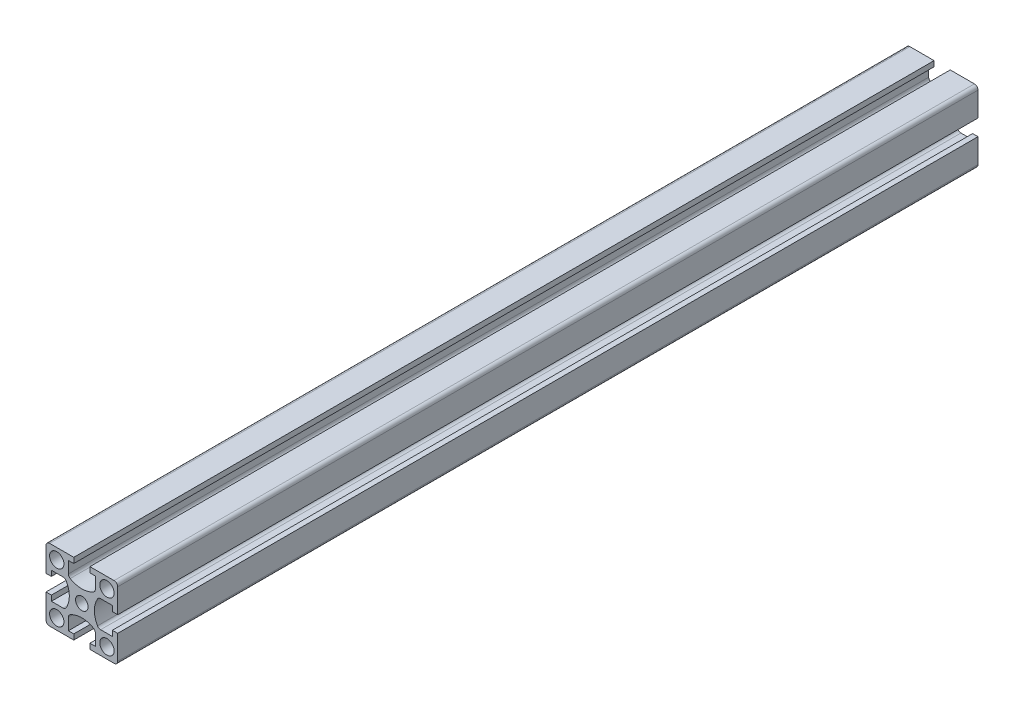
SolidWorks part; units mm, degrees
ref_plane "Front Plane" through (0, 0, 0) normal (0, 0, 1) x (1, 0, 0)
ref_plane "Top Plane" through (0, 0, 0) normal (0, 1, 0) x (1, 0, 0)
ref_plane "Right Plane" through (0, 0, 0) normal (1, 0, 0) x (0, 0, -1)
sketch "Sketch1" plane through (0, 0, 0) normal (0, 0, 1) x (1, 0, 0)
  line L64 (-12.5, 11.25) -> (-12.5, 2.8125)
  line L65 (-12.5, 2.8125) -> (-10.625, 2.8125)
  line L66 (-10.625, 2.8125) -> (-10.625, 4.6875)
  line L67 (-10.625, 4.6875) -> (-6.5461, 4.6875)
  line L68 (-6.5461, -4.6875) -> (-10.625, -4.6875)
  line L69 (-10.625, -4.6875) -> (-10.625, -2.8125)
  line L70 (-10.625, -2.8125) -> (-12.5, -2.8125)
  line L71 (-12.5, -2.8125) -> (-12.5, -11.25)
  line L72 (-11.25, -12.5) -> (-2.8125, -12.5)
  line L73 (-2.8125, -12.5) -> (-2.8125, -10.625)
  line L74 (-2.8125, -10.625) -> (-4.6875, -10.625)
  line L75 (-4.6875, -10.625) -> (-4.6875, -6.5461)
  line L76 (4.6875, -6.5461) -> (4.6875, -10.625)
  line L77 (4.6875, -10.625) -> (2.8125, -10.625)
  line L78 (2.8125, -10.625) -> (2.8125, -12.5)
  line L79 (2.8125, -12.5) -> (11.25, -12.5)
  line L80 (12.5, -11.25) -> (12.5, -2.8125)
  line L81 (12.5, -2.8125) -> (10.625, -2.8125)
  line L82 (10.625, -2.8125) -> (10.625, -4.6875)
  line L83 (10.625, -4.6875) -> (6.5461, -4.6875)
  line L84 (6.5461, 4.6875) -> (10.625, 4.6875)
  line L85 (10.625, 4.6875) -> (10.625, 2.8125)
  line L86 (10.625, 2.8125) -> (12.5, 2.8125)
  line L87 (12.5, 2.8125) -> (12.5, 11.25)
  line L88 (11.25, 12.5) -> (2.8125, 12.5)
  line L89 (2.8125, 12.5) -> (2.8125, 10.625)
  line L90 (2.8125, 10.625) -> (4.6875, 10.625)
  line L91 (4.6875, 10.625) -> (4.6875, 6.5461)
  line L92 (-4.6875, 6.5461) -> (-4.6875, 10.625)
  line L93 (-4.6875, 10.625) -> (-2.8125, 10.625)
  line L94 (-2.8125, 10.625) -> (-2.8125, 12.5)
  line L95 (-2.8125, 12.5) -> (-11.25, 12.5)
  circle A5 centre (-8.75, -8.75) radius 2.5
  circle A6 centre (8.75, -8.75) radius 2.5
  circle A7 centre (8.75, 8.75) radius 2.5
  circle A8 centre (0, 0) radius 2.1875
  circle A9 centre (-8.75, 8.75) radius 2.5
  arc A32 (-11.25, 12.5) -> (-12.5, 11.25) centre (-11.25, 11.25) ccw
  arc A33 (-5.4635, 4.0625) -> (-6.5461, 4.6875) centre (-6.5461, 3.4375) ccw
  arc A34 (-5.4635, -4.0625) -> (-5.4635, 4.0625) centre (-12.5, 0) ccw
  arc A35 (-6.5461, -4.6875) -> (-5.4635, -4.0625) centre (-6.5461, -3.4375) ccw
  arc A36 (-12.5, -11.25) -> (-11.25, -12.5) centre (-11.25, -11.25) ccw
  arc A37 (-4.0625, -5.4635) -> (-4.6875, -6.5461) centre (-3.4375, -6.5461) ccw
  arc A38 (4.0625, -5.4635) -> (-4.0625, -5.4635) centre (0, -12.5) ccw
  arc A39 (4.6875, -6.5461) -> (4.0625, -5.4635) centre (3.4375, -6.5461) ccw
  arc A40 (11.25, -12.5) -> (12.5, -11.25) centre (11.25, -11.25) ccw
  arc A41 (5.4635, -4.0625) -> (6.5461, -4.6875) centre (6.5461, -3.4375) ccw
  arc A42 (5.4635, 4.0625) -> (5.4635, -4.0625) centre (12.5, 0) ccw
  arc A43 (6.5461, 4.6875) -> (5.4635, 4.0625) centre (6.5461, 3.4375) ccw
  arc A44 (12.5, 11.25) -> (11.25, 12.5) centre (11.25, 11.25) ccw
  arc A45 (4.0625, 5.4635) -> (4.6875, 6.5461) centre (3.4375, 6.5461) ccw
  arc A46 (-4.0625, 5.4635) -> (4.0625, 5.4635) centre (0, 12.5) ccw
  arc A47 (-4.6875, 6.5461) -> (-4.0625, 5.4635) centre (-3.4375, 6.5461) ccw
extrude "Boss-Extrude1" add sketch "Sketch1" along normal blind 300
